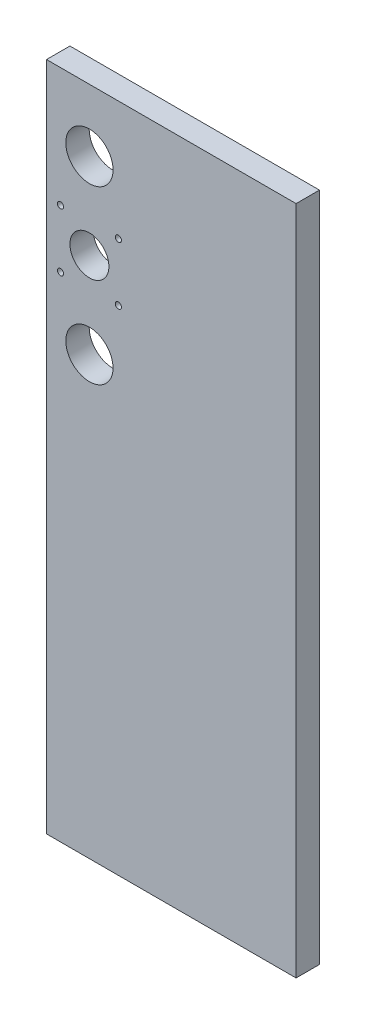
SolidWorks part; units mm, degrees
material "Balsa"
ref_plane "Front Plane" through (0, 0, 0) normal (0, 0, 1) x (1, 0, 0)
ref_plane "Top Plane" through (0, 0, 0) normal (0, 1, 0) x (1, 0, 0)
ref_plane "Right Plane" through (0, 0, 0) normal (1, 0, 0) x (0, 0, -1)
sketch "Sketch1" plane through (0, 0, 0) normal (0, 0, 1) x (1, 0, 0)
  line L1 (0, 0) -> (203.2, 0)
  line L2 (0, 0) -> (0, 546.1)
  line L3 (0, 546.1) -> (203.2, 546.1)
  line L4 (203.2, 0) -> (203.2, 546.1)
  dimension "D1" = 203.2
  dimension "D2" = 546.1
extrude "Boss-Extrude1" add sketch "Sketch1" along normal blind 19.05
sketch "Sketch2" plane through (0, 0, 0) normal (0, 0, -1) x (-1, 0, 0)
  line L0 (-101.6, 546.1) -> (-101.6, 0) construction
  line L1 (-203.2, 546.1) -> (0, 546.1) construction
  line L2 (0, 0) -> (-203.2, 0) construction
  line L3 (-174.63, 546.1) -> (-174.63, 0) construction
  line L4 (-34.925, 546.1) -> (-34.925, 0) construction
  circle A0 centre (-34.925, 495.3) radius 19.2405
  circle A1 centre (-34.925, 355.6) radius 19.2405
  dimension "D1" = 38.481
  dimension "D3" = 50.8
  dimension "D2" = 139.7
  dimension "D4" = 73.03
  dimension "D5" = 66.675
extrude "Cut-Extrude1" cut sketch "Sketch2" against normal through all
sketch "Esquisse1" plane through (0, 0, 0) normal (0, 0, -1) x (-1, 0, 0)
  line L0 (-58.4962, 449.0212) -> (-11.3538, 401.8788) construction
  line L1 (-58.4962, 401.8788) -> (-11.3538, 401.8788) construction
  line L2 (-58.4962, 401.8788) -> (-58.4962, 449.0212) construction
  line L3 (-58.4962, 449.0212) -> (-11.3538, 449.0212) construction
  line L4 (-11.3538, 401.8788) -> (-11.3538, 449.0212) construction
  line L5 (-34.925, 495.3) -> (-34.925, 425.45) construction
  line L6 (-34.925, 425.45) -> (-34.925, 495.3) construction
  line L7 (-34.925, 425.45) -> (-34.925, 355.6) construction
  circle A1 centre (-34.925, 425.45) radius 15.875
  circle A2 centre (-58.4962, 449.0212) radius 2.5
  circle A3 centre (-11.3538, 449.0212) radius 2.5
  circle A4 centre (-11.3538, 401.8788) radius 2.5
  circle A5 centre (-58.4962, 401.8788) radius 2.5
  point P9 (-34.925, 425.45)
  dimension "D1" = 31.75
  dimension "D2" = 47.1424
extrude "Enlèv. mat.-Extru.1" cut sketch "Esquisse1" against normal up to next
